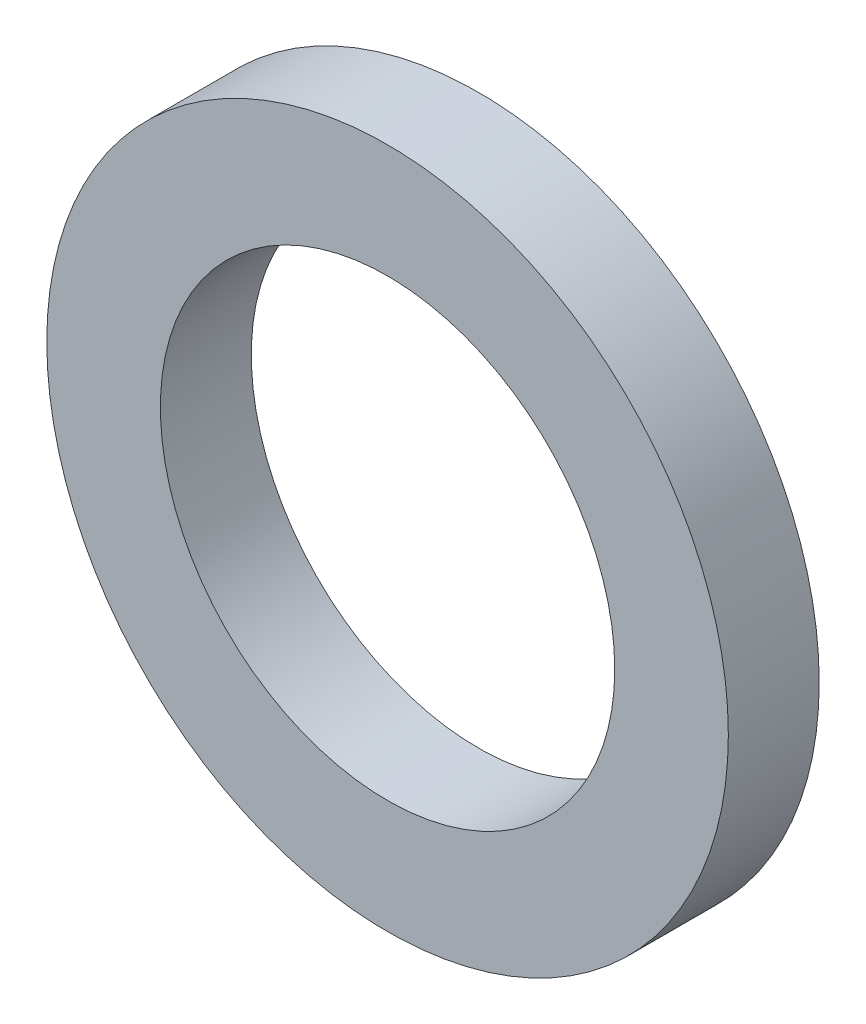
SolidWorks part; units mm, degrees
material "Custom Plastic"
ref_plane "Front Plane" through (0, 0, 0) normal (0, 0, 1) x (1, 0, 0)
ref_plane "Top Plane" through (0, 0, 0) normal (0, 1, 0) x (1, 0, 0)
ref_plane "Right Plane" through (0, 0, 0) normal (1, 0, 0) x (0, 0, -1)
sketch "Sketch1" plane through (0, 0, 0) normal (0, 0, 1) x (1, 0, 0)
  circle A0 centre (0, 0) radius 5
  circle A1 centre (0, 0) radius 7.5
  dimension "D1" = 10
  dimension "D2" = 15
extrude "Boss-Extrude1" add sketch "Sketch1" along normal blind 2
